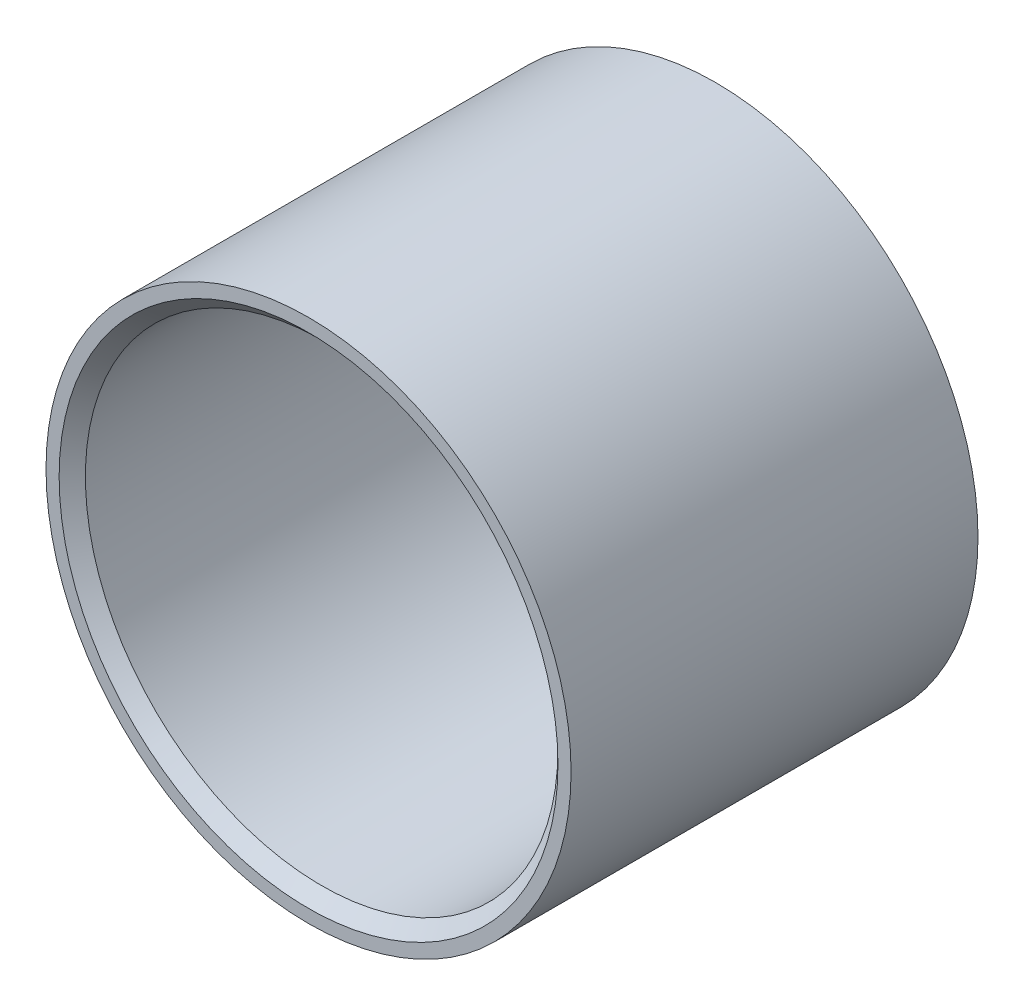
SolidWorks part; units mm, degrees
ref_plane "Ön Düzlem" through (0, 0, 0) normal (0, 0, 1) x (1, 0, 0)
ref_plane "Üst Düzlem" through (0, 0, 0) normal (0, 1, 0) x (1, 0, 0)
ref_plane "Sağ Düzlem" through (0, 0, 0) normal (1, 0, 0) x (0, 0, -1)
sketch "Çizim1" plane through (0, 0, 0) normal (0, 0, 1) x (1, 0, 0)
  circle A0 centre (0, 0) radius 9
  circle A1 centre (0, 0) radius 10
  dimension "D1" = 18
  dimension "D2" = 1
extrude "Yükseklik-Ekstrüzyon1" add sketch "Çizim1" along normal blind 15.5
chamfer "Pah1" distance 0.5 angle 45 1 edges at (9, 0, 15.5)
